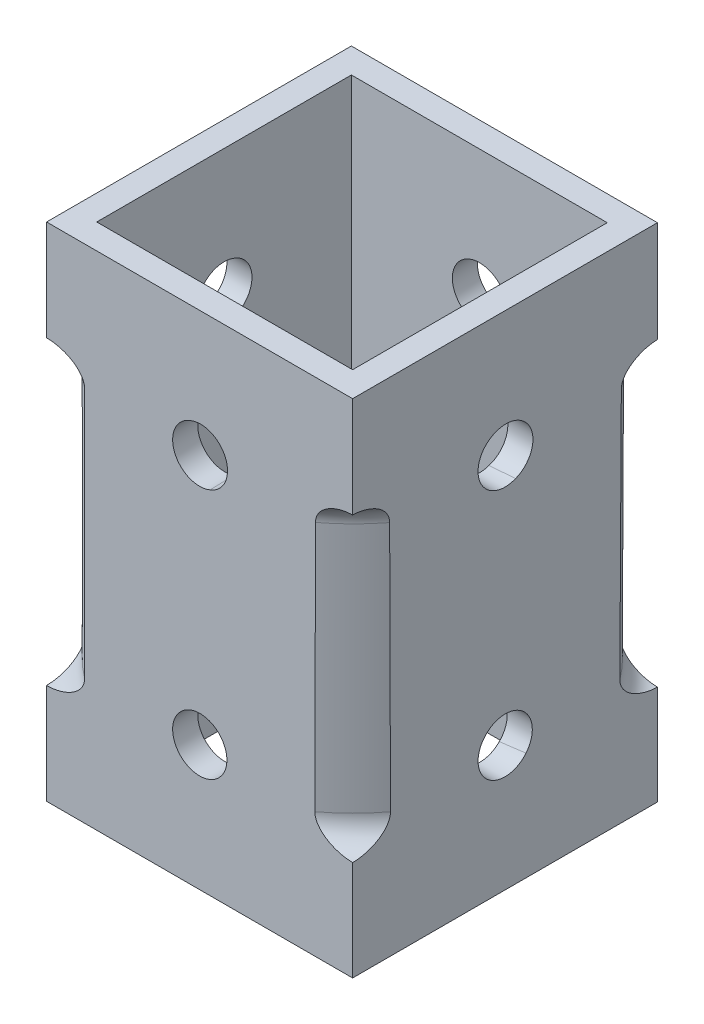
SolidWorks part; units mm, degrees
ref_plane "Front Plane" through (0, 0, 0) normal (0, 0, 1) x (1, 0, 0)
ref_plane "Top Plane" through (0, 0, 0) normal (0, 1, 0) x (1, 0, 0)
ref_plane "Right Plane" through (0, 0, 0) normal (1, 0, 0) x (0, 0, -1)
sketch "Sketch1" plane through (0, 0, 0) normal (0, 1, 0) x (1, 0, 0)
  line L0 (12.2, 12.15) -> (-12.2, 12.15)
  line L1 (10.2, -10.15) -> (-10.2, -10.15)
  line L2 (10.2, -10.15) -> (10.2, 10.15)
  line L3 (10.2, 10.15) -> (-10.2, 10.15)
  line L4 (-10.2, -10.15) -> (-10.2, 10.15)
  line L5 (10.2, -10.15) -> (-10.2, 10.15) construction
  line L6 (10.2, 10.15) -> (-10.2, -10.15) construction
  line L7 (-12.2, -12.15) -> (-12.2, 12.15)
  line L8 (12.2, -12.15) -> (-12.2, -12.15)
  line L9 (12.2, -12.15) -> (12.2, 12.15)
  point P0 (0, 0)
  dimension "D1" = 20.4
  dimension "D2" = 20.3
  dimension "D3" = 2
extrude "Boss-Extrude1" add sketch "Sketch1" along normal blind 40
ref_plane "Plane1" through (0, 0, 0) normal (0.7057, 0, 0.7086) x (0.7086, 0, -0.7057)
sketch "Sketch2" plane through (0, 0, 0) normal (0.7057, 0, 0.7086) x (0.7086, 0, -0.7057)
  line L0 (-17.2181, 10) -> (-17.2181, 30) construction
  line L1 (-17.2181, 40) -> (-17.2181, 0) construction
  line L2 (-19.2181, 10) -> (-19.2181, 30)
  line L3 (-15.2181, 10) -> (-15.2181, 30)
  line L4 (0.0707, 40) -> (0, 0) construction
  arc A0 (-19.2181, 10) -> (-15.2181, 10) centre (-17.2181, 10) ccw
  arc A1 (-15.2181, 30) -> (-19.2181, 30) centre (-17.2181, 30) ccw
  point P4 (-17.2181, 20)
  dimension "D2" = 2
  dimension "D1" = 20
revolve "Cut-Revolve1" cut sketch "Sketch2" angle 360 about L4
sketch "Sketch3" plane through (0, 0, -10.15) normal (0, 0, 1) x (1, 0, 0)
  line L0 (0, 0) -> (0, 40) construction
  line L1 (-12.2, 40) -> (12.2, 40) construction
  circle A0 centre (0, 30) radius 2.15
  circle A1 centre (0, 10) radius 2.15
  point P11 (0, 20)
  dimension "D3" = 4.3
  dimension "D1" = 10
  dimension "D2" = 10
extrude "Cut-Extrude1" cut sketch "Sketch3" against normal blind 40 and the other way blind 40
pattern_circular "CirPattern1" count 4 over 360 about axis through (0.0501, 40, -0.0499) along (-0.0013, -1, 0.0012) of "Cut-Extrude1"
